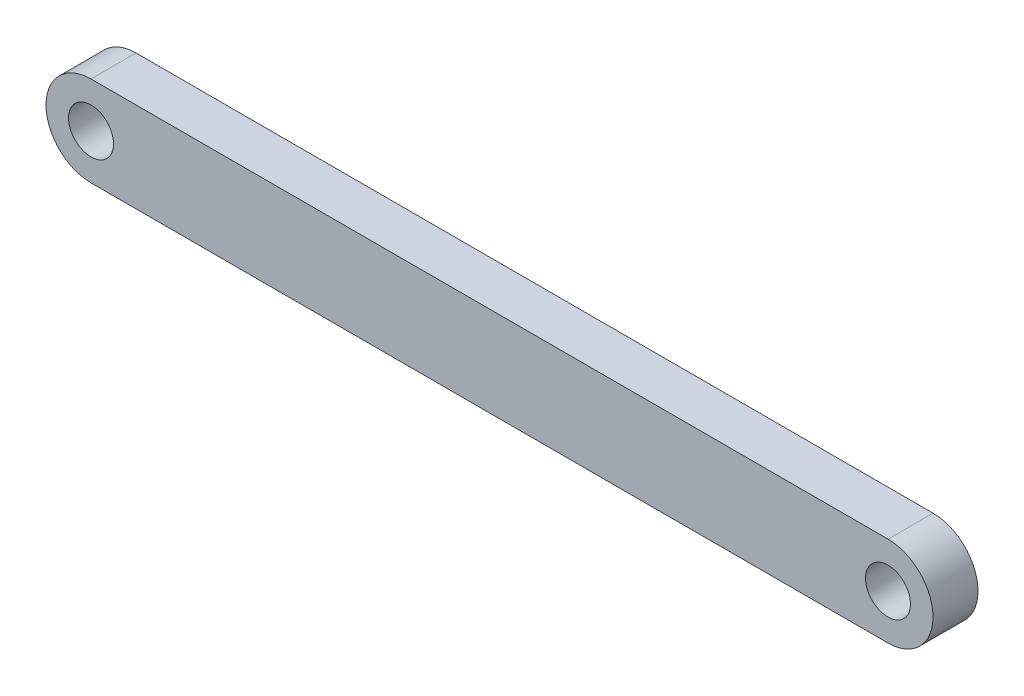
SolidWorks part; units mm, degrees
ref_plane "前基準面" through (0, 0, 0) normal (0, 0, 1) x (1, 0, 0)
ref_plane "上基準面" through (0, 0, 0) normal (0, 1, 0) x (1, 0, 0)
ref_plane "右基準面" through (0, 0, 0) normal (1, 0, 0) x (0, 0, -1)
sketch "草圖1" plane through (0, 0, 0) normal (0, 0, 1) x (1, 0, 0)
  line L0 (-17.71, 2.0009) -> (17.71, 2.0009)
  line L1 (-17.71, -1.9991) -> (17.71, -1.9991)
  arc A0 (-17.71, 2.0009) -> (-17.71, -1.9991) centre (-17.71, 0.0009) ccw
  arc A1 (17.71, -1.9991) -> (17.71, 2.0009) centre (17.71, 0.0009) ccw
  circle A2 centre (-17.71, 0.0009) radius 1
  circle A3 centre (17.71, 0.0009) radius 1
  dimension "D1" = 35.42
  dimension "D2" = 2
  dimension "D3" = 2
  dimension "D4" = 2
  dimension "D5" = 17.71
extrude "填料-伸長1" add sketch "草圖1" along normal blind 2
